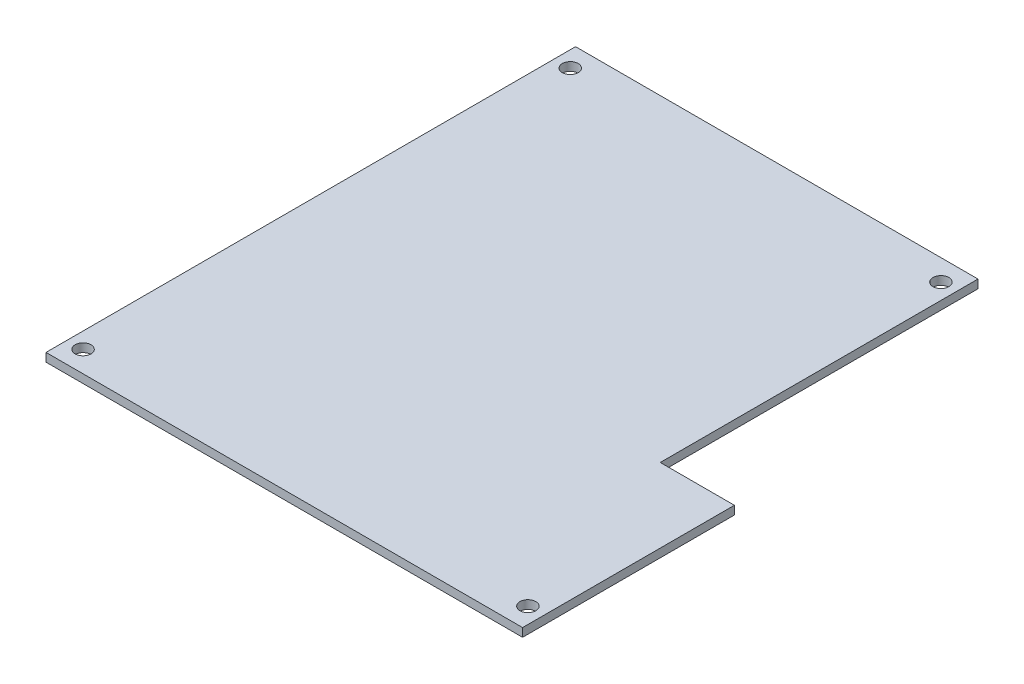
SolidWorks part; units mm, degrees
ref_plane "Ön Düzlem" through (0, 0, 0) normal (0, 0, 1) x (1, 0, 0)
ref_plane "Üst Düzlem" through (0, 0, 0) normal (0, 1, 0) x (1, 0, 0)
ref_plane "Sağ Düzlem" through (0, 0, 0) normal (1, 0, 0) x (0, 0, -1)
sketch "Çizim1" plane through (0, 0, 0) normal (0, 1, 0) x (1, 0, 0)
  line L0 (90, 0) -> (90, 40)
  line L1 (0, 0) -> (90, 0)
  line L2 (0, 0) -> (0, 100)
  line L3 (0, 100) -> (76, 100)
  line L5 (90, 40) -> (76, 40)
  line L6 (76, 40) -> (76, 100)
  dimension "D1" = 100
  dimension "D2" = 90
  dimension "D3" = 40
  dimension "D4" = 14
extrude "Yükseklik-Ekstrüzyon1" add sketch "Çizim1" along normal blind 1.6
sketch "Çizim2" plane through (0, 1.6, 0) normal (0, 1, 0) x (1, 0, 0)
  line L0 (0, 50) -> (76, 50) construction
  line L3 (0, 100) -> (0, 0) construction
  line L4 (76, 40) -> (76, 100) construction
  line L5 (38, 100) -> (38, 0) construction
  line L6 (76, 100) -> (0, 100) construction
  line L7 (0, 0) -> (90, 0) construction
  line L8 (45, 0) -> (45, 100) construction
  circle A0 centre (3, 96) radius 1.5
  circle A1 centre (3, 4) radius 1.5
  circle A2 centre (73, 96) radius 1.5
  circle A3 centre (87, 4) radius 1.5
  dimension "D1" = 96
  dimension "D3" = 3
  dimension "D2" = 3
extrude "Kes-Ekstrüzyon1" cut sketch "Çizim2" against normal blind 10
